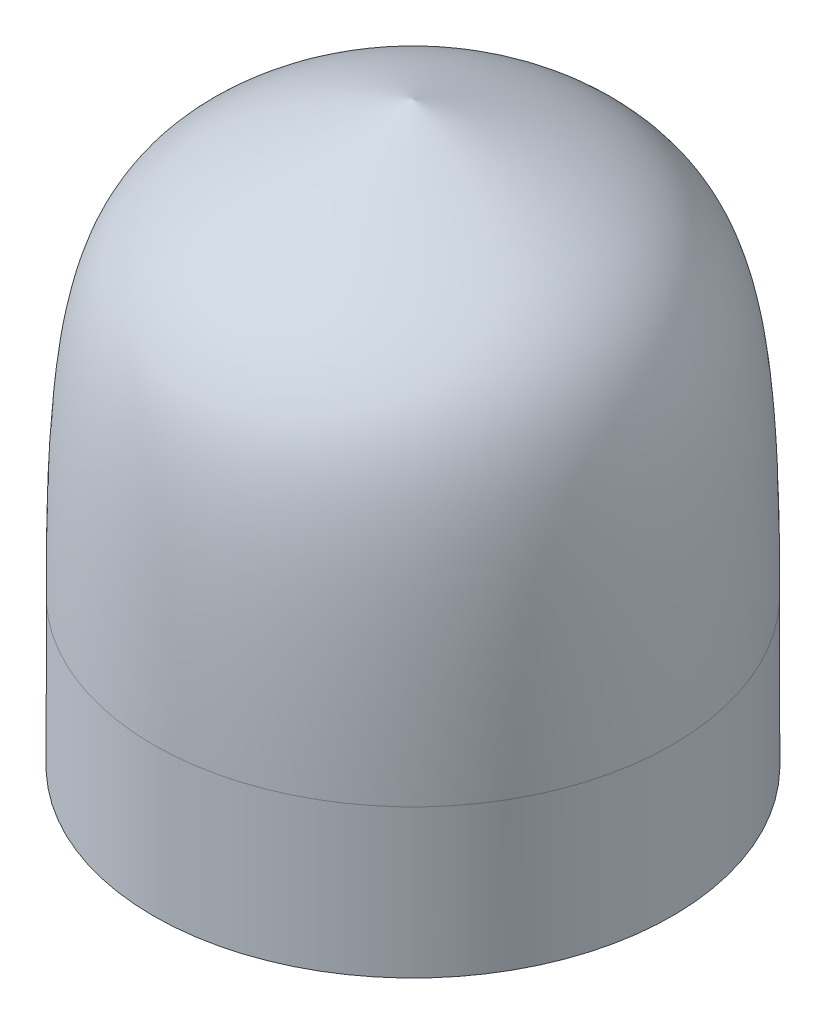
SolidWorks part; units mm, degrees
ref_plane "Front Plane" through (0, 0, 0) normal (0, 0, 1) x (1, 0, 0)
ref_plane "Top Plane" through (0, 0, 0) normal (0, 1, 0) x (1, 0, 0)
ref_plane "Right Plane" through (0, 0, 0) normal (1, 0, 0) x (0, 0, -1)
sketch "Sketch6" plane through (0, 0, 0) normal (0, 1, 0) x (1, 0, 0)
  circle A0 centre (0, 0) radius 8.89
  dimension "D1" = 17.78
extrude "Boss-Extrude8" add sketch "Sketch6" along normal blind 5.08
sketch "Sketch8" plane through (0, 0, 0) normal (0, 0, 1) x (1, 0, 0)
  line L0 (0, 5.08) -> (0, 19.7916)
  line L1 (8.89, 5.08) -> (-8.89, 5.08) construction
  line L2 (0, 5.08) -> (-8.89, 5.08)
  conic Q0 (-8.89, 5.08) -> (0, 19.7916) control (-8.89, 16.8008) rho 0.7
  dimension "D2" = 17.189
revolve "Revolve3" add sketch "Sketch8" angle 360 about L0
